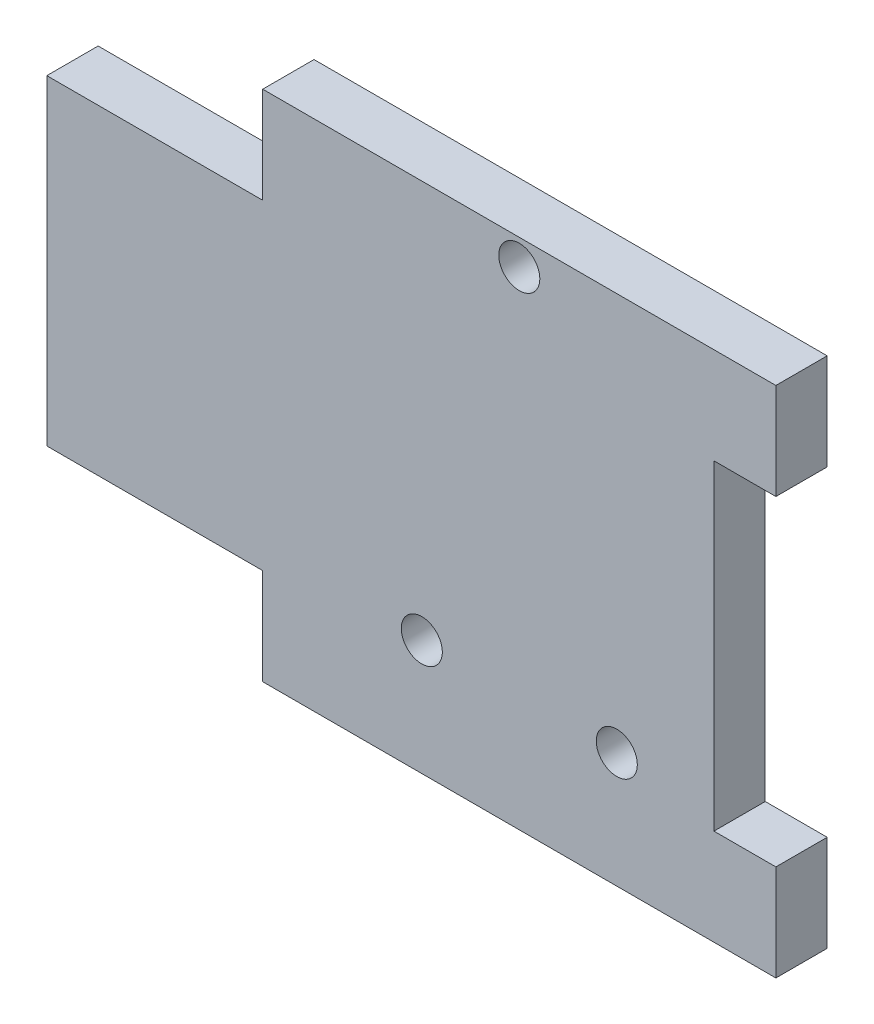
SolidWorks part; units mm, degrees
ref_plane "Front Plane" through (0, 0, 0) normal (0, 0, 1) x (1, 0, 0)
ref_plane "Top Plane" through (0, 0, 0) normal (0, 1, 0) x (1, 0, 0)
ref_plane "Right Plane" through (0, 0, 0) normal (1, 0, 0) x (0, 0, -1)
sketch "Sketch1" plane through (0, 0, 0) normal (0, 0, 1) x (-1, 0, 0)
  line L0 (-20, 40) -> (20, 40)
  line L1 (20, 40) -> (20, 32.5)
  line L2 (0, 40) -> (0, 0) construction
  line L3 (-7.6, 31) -> (0, 31) construction
  line L5 (20, 7.5) -> (20, 0)
  line L6 (20, 0) -> (-20, 0)
  line L7 (-20, 0) -> (-20, 7.5)
  line L8 (-20, 7.5) -> (-15.1716, 7.5)
  line L9 (-15.1716, 7.5) -> (-15.1716, 32.5)
  line L10 (-15.1716, 32.5) -> (-20, 32.5)
  line L11 (-20, 32.5) -> (-20, 40)
  line L13 (20, 32.5) -> (36.8284, 32.5)
  line L15 (20, 7.5) -> (36.8284, 7.5)
  line L16 (36.8284, 32.5) -> (36.8284, 7.5)
  circle A0 centre (-7.6, 31) radius 1.6
  circle A1 centre (7.6, 31) radius 1.6
  circle A2 centre (0, 2) radius 1.6
  dimension "D1" = 40
  dimension "D2" = 35.1716
  dimension "D3" = 52
  dimension "D4" = 7.6
  dimension "D5" = 29
  dimension "D6" = 9
extrude "Boss-Extrude1" add sketch "Sketch1" along normal blind 4
